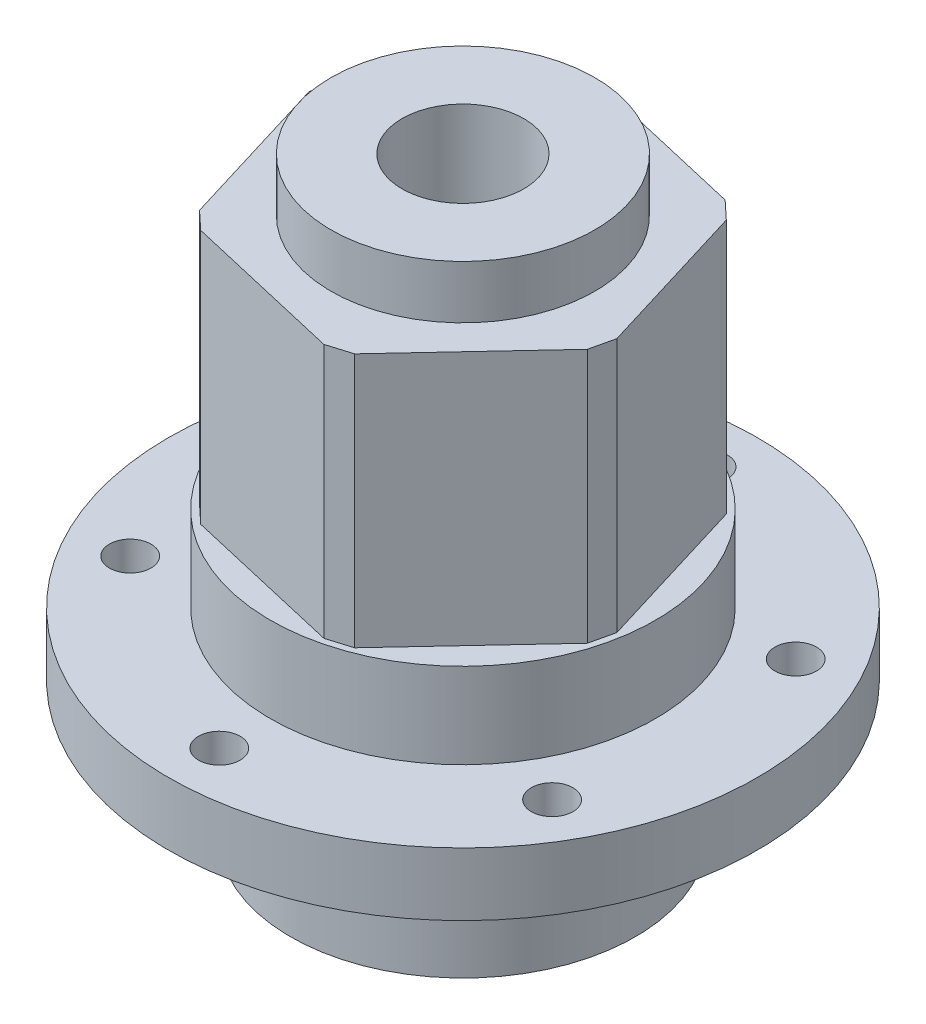
SolidWorks part; units mm, degrees
ref_plane "Piano frontale" through (0, 0, 0) normal (0, 0, 1) x (1, 0, 0)
ref_plane "Piano superiore" through (0, 0, 0) normal (0, 1, 0) x (1, 0, 0)
ref_plane "Piano destro" through (0, 0, 0) normal (1, 0, 0) x (0, 0, -1)
sketch "Schizzo1" plane through (0, 0, 0) normal (0, 0, 1) x (1, 0, 0)
  line L0 (0, 0) -> (0, -14) construction
  line L1 (0, 0) -> (9.485, 0)
  line L2 (9.485, 0) -> (9.485, -4.2)
  line L3 (9.485, -4.2) -> (14.505, -4.2)
  line L4 (14.505, -4.2) -> (14.505, -7.3)
  line L5 (14.505, -7.3) -> (10.745, -7.3)
  line L6 (8.495, -9.55) -> (8.495, -14)
  line L7 (8.495, -14) -> (0, -14)
  line L8 (0, 0) -> (0, -14)
  arc A0 (10.745, -7.3) -> (8.495, -9.55) centre (10.745, -9.55) ccw
  point P11 (8.495, -7.3)
  dimension "D7" = 2.25
  dimension "D1" = 18.97
  dimension "D2" = 29.01
  dimension "D3" = 16.99
  dimension "D4" = 3.1
  dimension "D5" = 14
  dimension "D6" = 6.7
revolve "Rivoluzione1" add sketch "Schizzo1" angle 360 about L0
sketch "Schizzo2" plane through (0, 0, 0) normal (0, 1, 0) x (1, 0, 0)
  line L0 (2.09, -8.9379) -> (3.2498, -8.5845)
  line L1 (-9.0593, 1.4778) -> (-6.6954, -6.279)
  line L2 (-5.8095, -7.1066) -> (2.09, -8.9379)
  line L3 (3.2498, -8.5845) -> (8.7854, -2.6589)
  line L4 (9.0593, -1.4778) -> (6.6954, 6.279)
  line L5 (5.8095, 7.1066) -> (-2.09, 8.9379)
  line L6 (-3.2498, 8.5845) -> (-8.7854, 2.6589)
  line L7 (-6.6954, -6.279) -> (-5.8095, -7.1066)
  line L8 (8.7854, -2.6589) -> (9.0593, -1.4778)
  line L9 (6.6954, 6.279) -> (5.8095, 7.1066)
  line L10 (-2.09, 8.9379) -> (-3.2498, 8.5845)
  line L11 (-8.7854, 2.6589) -> (-9.0593, 1.4778)
  circle A0 centre (0, 0) radius 9.485 construction
  point P2 (-9.2633, 2.1474)
  point P3 (-6.4914, -6.9485)
  point P4 (2.7719, -9.096)
  point P5 (9.2633, -2.1474)
  point P6 (6.4914, 6.9485)
  point P7 (-2.7719, 9.096)
  dimension "D1" = 16.47
extrude "Estrusione-Estrusione1" add sketch "Schizzo2" along normal blind 12.54
sketch "Schizzo3" plane through (0, 12.54, 0) normal (0, 1, 0) x (1, 0, 0)
  circle A0 centre (0, 0) radius 6.5
  dimension "D1" = 13
extrude "Estrusione-Estrusione2" add sketch "Schizzo3" along normal blind 2.62
sketch "Schizzo4" plane through (0, 15.16, 0) normal (0, 1, 0) x (1, 0, 0)
  circle A0 centre (0, 0) radius 3
  dimension "D1" = 6
extrude "Taglio-Estrusione1" cut sketch "Schizzo4" against normal through all
hole_wizard "Foro filettato M2.5x0.45-1" positions "Schizzo6" profile "Schizzo5" tap size "M2.5x0.45" standard "Ansi Metric" end condition through all
sketch "Schizzo6" plane through (0, -4.2, 0) normal (0, 1, 0) x (1, 0, 0)
  circle A1 centre (0, 0) radius 12
  point P0 (0, -12)
  point P15 (-10.3923, -6)
  point P16 (-10.3923, 6)
  point P17 (0, 12)
  point P18 (10.3923, 6)
  point P19 (10.3923, -6)
  point P20 (0, 0)
  dimension "D1" = 24
  dimension "D2" = 6
sketch "Schizzo5" plane through (0, -4.2, 12) normal (1, 0, 0) x (0, 0, 1)
  line L0 (0, 0) -> (0, 9.8)
  line L1 (0, 9.8) -> (1.025, 9.8)
  line L2 (1.025, 9.8) -> (1.025, 0)
  line L5 (1.025, 0) -> (0, 0)
  line L11 (0, -6.35) -> (0, 107.95) construction
  dimension "Thru Tap Drill Dia." = 2.05
  dimension "Thru Tap Drill Depth" = 9.8
cosmetic thread "Filettatura del foro1" parameters "D2"=2.5
cosmetic thread "Filettatura del foro2" parameters "D2"=2.5
cosmetic thread "Filettatura del foro3" parameters "D2"=2.5
cosmetic thread "Filettatura del foro4" parameters "D2"=2.5
cosmetic thread "Filettatura del foro5" parameters "D2"=2.5
cosmetic thread "Filettatura del foro6" parameters "D2"=2.5
